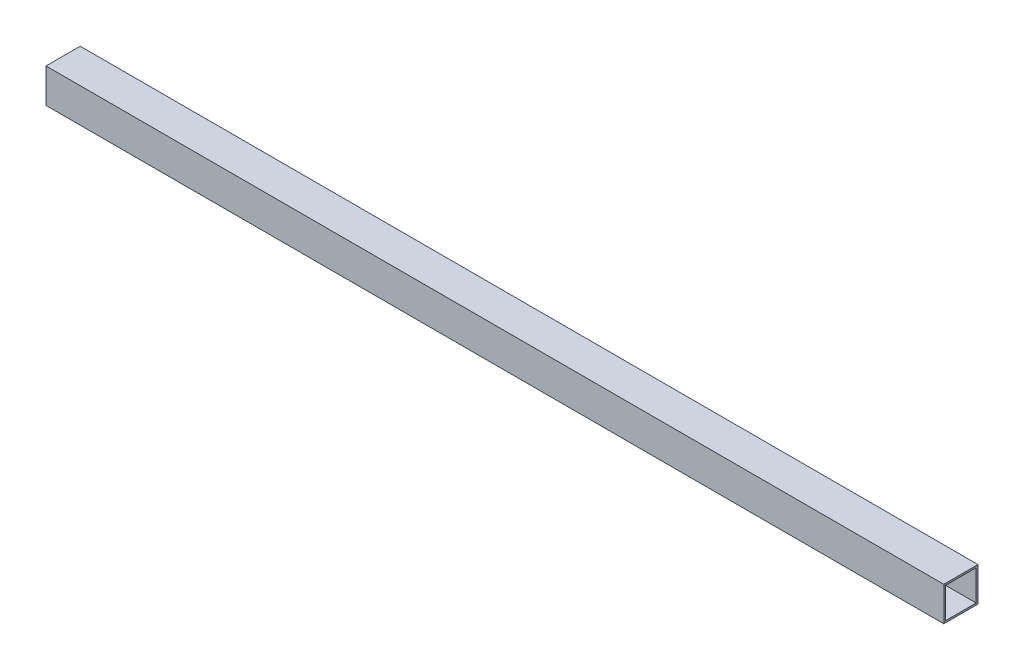
SolidWorks part; units mm, degrees
material "6063-O, Extruded Rod (SS)"
ref_plane "Front Plane" through (0, 0, 0) normal (0, 0, 1) x (1, 0, 0)
ref_plane "Top Plane" through (0, 0, 0) normal (0, 1, 0) x (1, 0, 0)
ref_plane "Right Plane" through (0, 0, 0) normal (1, 0, 0) x (0, 0, -1)
sketch "Sketch1" plane through (0, 0, 0) normal (1, 0, 0) x (0, 0, -1)
  line L0 (-8.525, 8.525) -> (8.525, 8.525)
  line L1 (-9.525, 9.525) -> (9.525, 9.525)
  line L2 (-9.525, 9.525) -> (-9.525, -9.525)
  line L3 (-9.525, -9.525) -> (9.525, -9.525)
  line L4 (9.525, 9.525) -> (9.525, -9.525)
  line L5 (-9.525, 9.525) -> (9.525, -9.525) construction
  line L6 (-9.525, -9.525) -> (9.525, 9.525) construction
  line L7 (8.525, 8.525) -> (8.525, -8.525)
  line L8 (-8.525, -8.525) -> (8.525, -8.525)
  line L9 (-8.525, 8.525) -> (-8.525, -8.525)
  point P0 (0, 0)
  dimension "D1" = 19.05
  dimension "D2" = 19.05
  dimension "D3" = 1
extrude "Boss-Extrude1" add sketch "Sketch1" along normal blind 500
